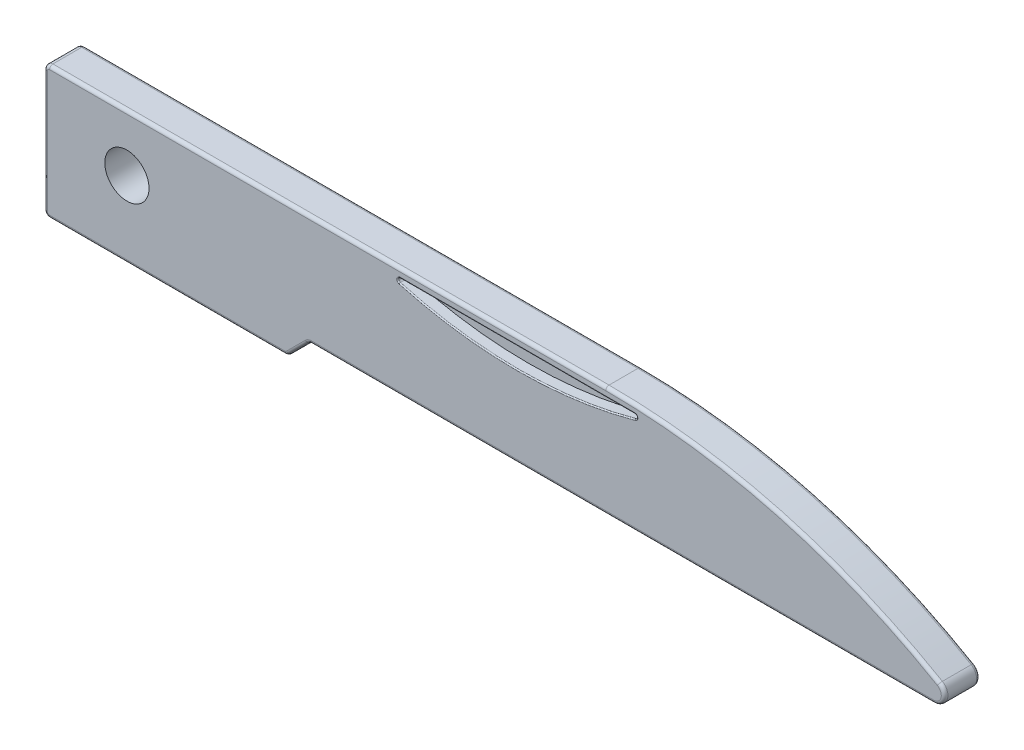
SolidWorks part; units mm, degrees
ref_plane "Front Plane" through (0, 0, 0) normal (0, 0, 1) x (1, 0, 0)
ref_plane "Top Plane" through (0, 0, 0) normal (0, 1, 0) x (1, 0, 0)
ref_plane "Right Plane" through (0, 0, 0) normal (1, 0, 0) x (0, 0, -1)
sketch "Sketch1" plane through (0, 0, 0) normal (0, 0, 1) x (1, 0, 0)
  line L0 (0, 0) -> (0, 6)
  line L1 (0, 6) -> (25.4169, 6)
  line L2 (42, 1) -> (12, 1)
  line L3 (12, 1) -> (11, 0)
  line L4 (11, 0) -> (0, 0)
  arc A0 (25.4169, 6) -> (42, 1) centre (25.4169, -24) cw
  point P6 (12, 0.9187)
  point P9 (12, 1.0056)
  point P10 (10.4018, 0)
  point P11 (12, 0.6868)
  dimension "D2" = 30
  dimension "D1" = 42
  dimension "D3" = 6
  dimension "D4" = 30
  dimension "D5" = 5
  dimension "D6" = 45
extrude "Boss-Extrude1" add sketch "Sketch1" along normal blind 1.6
fillet "Fillet1" radius 0.5 1 edges at (42, 1, 0.8)
fillet "Fillet2" radius 0.25 4 edges at (0, 6, 0.8) (12, 1, 0.8) (11, 0, 0.8) (0, 0, 0.8)
fillet "Fillet3" radius 0.15 22 edges at (0.0732, 0.0732, 0) (5.5732, 0, 0) (10.9921, 0.019, 0) (11.5, 0.5, 0) (12.0079, 0.981, 0) (26.1764, 1, 0) (40.732, 1.3698, 0) (33.2282, 4.9652, 0) (12.8334, 6, 0) (0.0732, 5.9268, 0) (0, 3, 0) (33.2282, 4.9652, 1.6) (40.732, 1.3698, 1.6) (26.1764, 1, 1.6) (12.0079, 0.981, 1.6) (11.5, 0.5, 1.6) (10.9921, 0.019, 1.6) (5.5732, 0, 1.6) (0.0732, 0.0732, 1.6) (0, 3, 1.6) (0.0732, 5.9268, 1.6) (12.8334, 6, 1.6)
sketch "Sketch2" plane through (0, 0, 1.6) normal (0, 0, 1) x (1, 0, 0)
  circle A0 centre (3.75, 3.45) radius 1
  dimension "D1" = 2
  dimension "D2" = 3.5
  dimension "D3" = 3.2
extrude "Cut-Extrude1" cut sketch "Sketch2" against normal through all
sketch "Sketch3" plane through (0, 0, 1.6) normal (0, 0, 1) x (1, 0, 0)
  line L0 (15.4169, 5.6) -> (27.4169, 5.6)
  line L1 (25.4169, 5.85) -> (0.25, 5.85) construction
  line L4 (25.4169, 6) -> (25.4169, 5.85) construction
  arc A0 (27.4169, 5.6) -> (15.4169, 5.6) centre (21.4169, 24.6788) cw
  dimension "D2" = 20
  dimension "D1" = 12
  dimension "D3" = 0.25
  dimension "D4" = 10
extrude "Cut-Extrude2" cut sketch "Sketch3" against normal blind 0.5
fillet "Fillet4" radius 0.1 2 edges at (15.4169, 5.6, 1.35) (27.4169, 5.6, 1.35)
fillet "Fillet5" radius 0.05 4 edges at (26.8248, 5.5135, 1.6) (21.4169, 4.6788, 1.6) (16.0089, 5.5135, 1.6) (21.4169, 5.6, 1.6)
